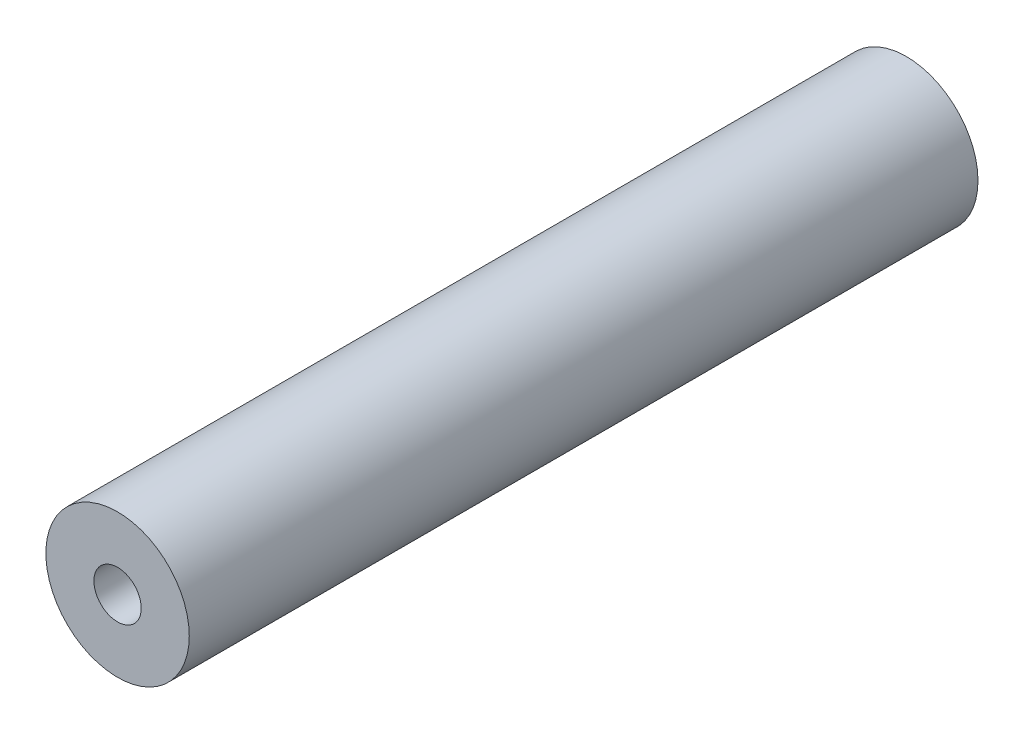
SolidWorks part; units mm, degrees
material "5052-H34"
ref_plane "正面" through (0, 0, 0) normal (0, 0, 1) x (1, 0, 0)
ref_plane "平面" through (0, 0, 0) normal (0, 1, 0) x (1, 0, 0)
ref_plane "右側面" through (0, 0, 0) normal (1, 0, 0) x (0, 0, -1)
sketch "ｽｹｯﾁ1" plane through (0, 0, 0) normal (0, 0, 1) x (1, 0, 0)
  circle A0 centre (0, 0) radius 5
  dimension "D1" = 10
extrude "ﾎﾞｽ - 押し出し1" add sketch "ｽｹｯﾁ1" along normal blind 55
sketch "ｽｹｯﾁ2" plane through (0, 0, 55) normal (0, 0, 1) x (1, 0, 0)
  circle A0 centre (0, 0) radius 1.65
  dimension "D1" = 3.3
extrude "ｶｯﾄ - 押し出し1" cut sketch "ｽｹｯﾁ2" against normal blind 10
sketch "ｽｹｯﾁ3" plane through (0, 0, 0) normal (0, 0, -1) x (-1, 0, 0)
  circle A0 centre (0, 0) radius 1.65
  dimension "D1" = 3.3
extrude "ｶｯﾄ - 押し出し2" cut sketch "ｽｹｯﾁ3" against normal blind 10
